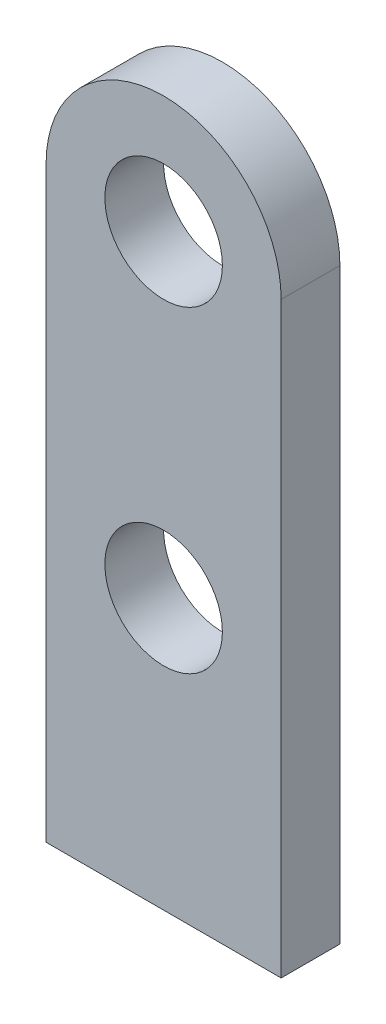
SolidWorks part; units mm, degrees
ref_plane "前视基准面" through (0, 0, 0) normal (0, 0, 1) x (1, 0, 0)
ref_plane "上视基准面" through (0, 0, 0) normal (0, 1, 0) x (1, 0, 0)
ref_plane "右视基准面" through (0, 0, 0) normal (1, 0, 0) x (0, 0, -1)
sketch "草图1" plane through (0, 0, 0) normal (0, 0, 1) x (1, 0, 0)
  line L0 (0, 0) -> (0, -54)
  line L1 (0, 0) -> (-20, 0)
  line L2 (-20, 0) -> (-20, -100)
  line L3 (-20, -100) -> (20, -100)
  line L4 (20, -100) -> (20, 0)
  circle A0 centre (0, 0) radius 10
  circle A1 centre (0, -54) radius 10
  circle A2 centre (0, 0) radius 20
extrude "凸台-拉伸2" add sketch "草图1" along normal blind 10
